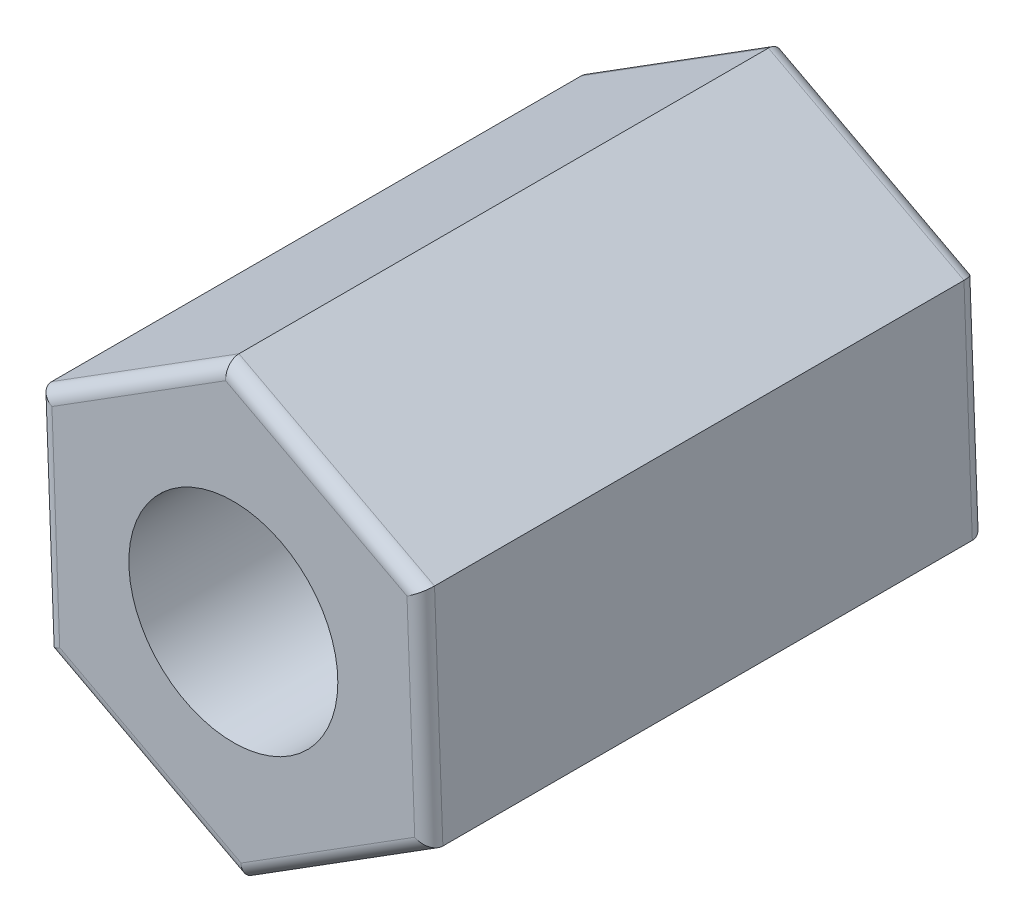
SolidWorks part; units mm, degrees
material "201 Annealed Stainless Steel (SS)"
ref_plane "Front Plane" through (0, 0, 0) normal (0, 0, 1) x (1, 0, 0)
ref_plane "Top Plane" through (0, 0, 0) normal (0, 1, 0) x (1, 0, 0)
ref_plane "Right Plane" through (0, 0, 0) normal (1, 0, 0) x (0, 0, -1)
sketch "Sketch2" plane through (0, 0, 0) normal (0, 0, 1) x (1, 0, 0)
  line L1 (-2.8079, 1.483) -> (-2.6882, -1.6902)
  line L2 (-2.6882, -1.6902) -> (0.1196, -3.1732)
  line L3 (0.1196, -3.1732) -> (2.8079, -1.483)
  line L4 (2.8079, -1.483) -> (2.6882, 1.6902)
  line L5 (2.6882, 1.6902) -> (-0.1196, 3.1732)
  line L6 (-0.1196, 3.1732) -> (-2.8079, 1.483)
  circle A0 centre (0, 0) radius 2.75 construction
  circle A1 centre (0, 0) radius 1.5
  dimension "D1" = 5.5
  dimension "D2" = 3
extrude "Boss-Extrude1" add sketch "Sketch2" along normal blind 8
fillet "Fillet1" radius 0.2 6 edges at (1.2843, 2.4317, 0) (2.748, 0.1036, 0) (1.4638, -2.3281, 0) (-1.2843, -2.4317, 0) (-2.748, -0.1036, 0) (-1.4638, 2.3281, 0)
fillet "Fillet2" radius 0.2 6 edges at (-1.2843, -2.4317, 8) (1.4638, -2.3281, 8) (2.748, 0.1036, 8) (1.2843, 2.4317, 8) (-1.4638, 2.3281, 8) (-2.748, -0.1036, 8)
